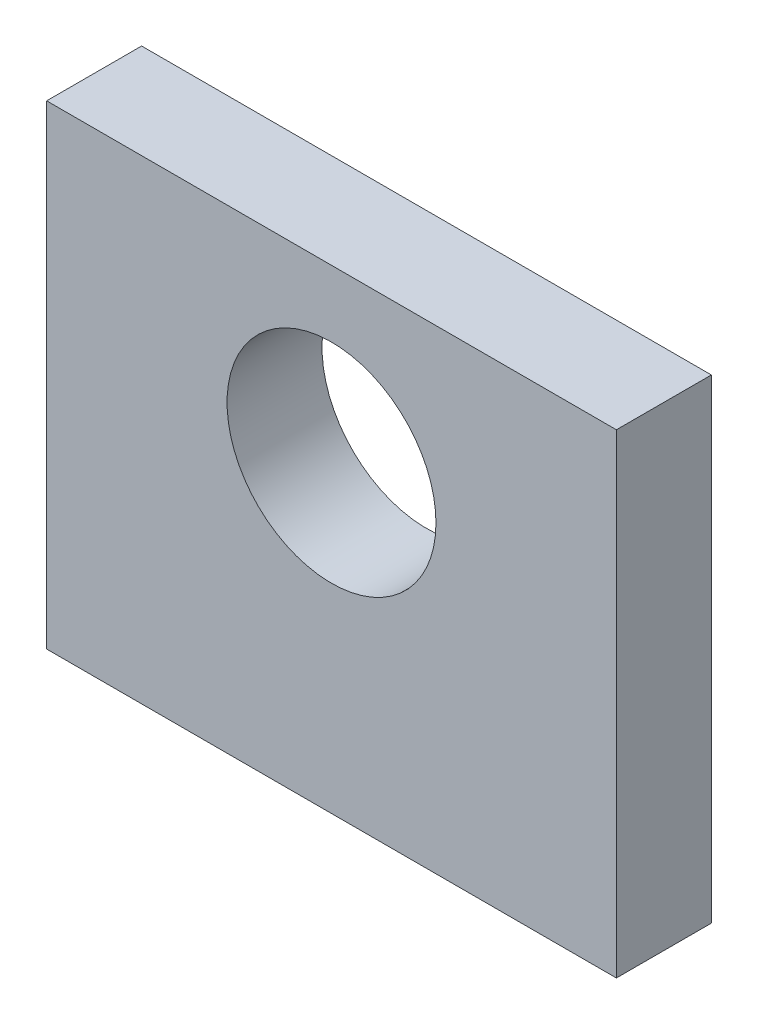
SolidWorks part; units mm, degrees
material "PTEG"
ref_plane "Alzado" through (0, 0, 0) normal (0, 0, 1) x (1, 0, 0)
ref_plane "Planta" through (0, 0, 0) normal (0, 1, 0) x (1, 0, 0)
ref_plane "Vista lateral" through (0, 0, 0) normal (1, 0, 0) x (0, 0, -1)
sketch "Croquis1" plane through (0, 0, 0) normal (0, 0, 1) x (1, 0, 0)
  line L1 (0, 0) -> (60, 0)
  line L2 (0, 0) -> (0, 50)
  line L3 (0, 50) -> (60, 50)
  line L4 (60, 0) -> (60, 50)
  circle A0 centre (30, 32) radius 11
  point P7 (30, 50)
  dimension "D3" = 22
  dimension "D1" = 60
  dimension "D2" = 50
  dimension "D4" = 18
extrude "Saliente-Extruir1" add sketch "Croquis1" along normal blind 10
